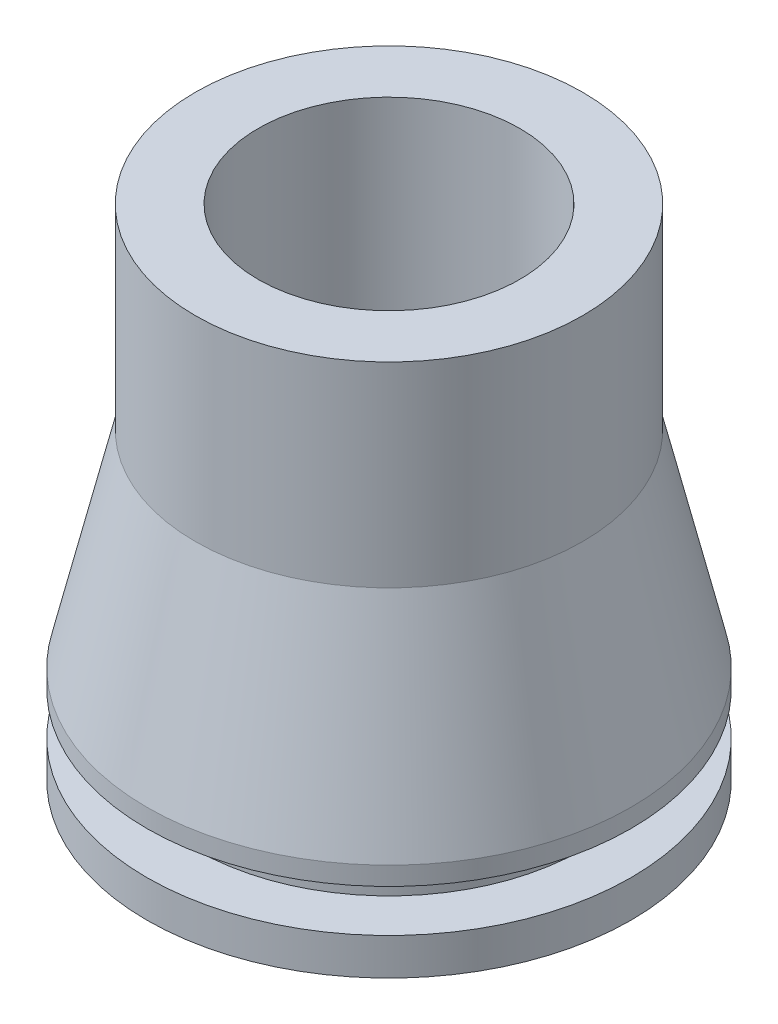
SolidWorks part; units mm, degrees
ref_plane "Front Plane" through (0, 0, 0) normal (0, 0, 1) x (1, 0, 0)
ref_plane "Top Plane" through (0, 0, 0) normal (0, 1, 0) x (1, 0, 0)
ref_plane "Right Plane" through (0, 0, 0) normal (1, 0, 0) x (0, 0, -1)
sketch "Sketch1" plane through (0, 0, 0) normal (0, 0, 1) x (1, 0, 0)
  line L0 (3.6004, 0) -> (3.6004, 13.7414)
  line L1 (3.6004, 13.7414) -> (5.3276, 13.7414)
  line L2 (5.3276, 13.7414) -> (5.3276, 8.3566)
  line L3 (5.3276, 8.3566) -> (6.6611, 2.6924)
  line L4 (6.6611, 2.6924) -> (6.6611, 2.1844)
  line L5 (6.6611, 2.1844) -> (5.3276, 2.1844)
  line L6 (5.3276, 2.1844) -> (5.3276, 1.016)
  line L7 (5.3276, 1.016) -> (6.6611, 1.016)
  line L8 (6.6611, 1.016) -> (6.6611, 0)
  line L9 (6.6611, 0) -> (3.6004, 0)
  line L10 (0, 0) -> (0, 27.3018) construction
  dimension "D1" = 3.6004
  dimension "D2" = 5.3276
  dimension "D3" = 6.6611
  dimension "D4" = 11.557
  dimension "D5" = 5.3848
  dimension "D6" = 0.508
  dimension "D7" = 1.1684
  dimension "D8" = 1.016
revolve "Revolve1" add sketch "Sketch1" angle 360 about L10
